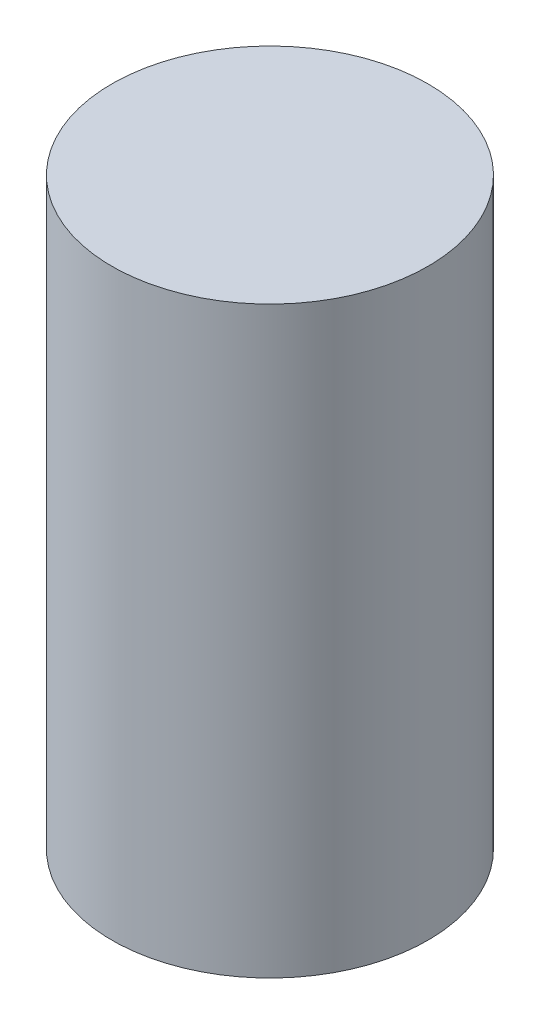
SolidWorks part; units mm, degrees
material "1060-H12 Rod (SS)"
ref_plane "Front Plane" through (0, 0, 0) normal (0, 0, 1) x (1, 0, 0)
ref_plane "Top Plane" through (0, 0, 0) normal (0, 1, 0) x (1, 0, 0)
ref_plane "Right Plane" through (0, 0, 0) normal (1, 0, 0) x (0, 0, -1)
sketch "Sketch1" plane through (0, 0, 0) normal (0, 1, 0) x (1, 0, 0)
  circle A0 centre (0, 0) radius 20.6375
extrude "Boss-Extrude1" add sketch "Sketch1" along normal blind 76.2
sketch "Sketch2" plane through (0, 0, 0) normal (0, -1, 0) x (1, 0, 0)
  line L0 (0, 0) -> (0, 33.8917) construction
  circle A0 centre (-10.16, 0) radius 3.175
  circle A1 centre (10.16, 0) radius 3.175
  dimension "D1" = 6.35
  dimension "D2" = 10.16
extrude "Cut-Extrude1" cut sketch "Sketch2" against normal blind 6.35
